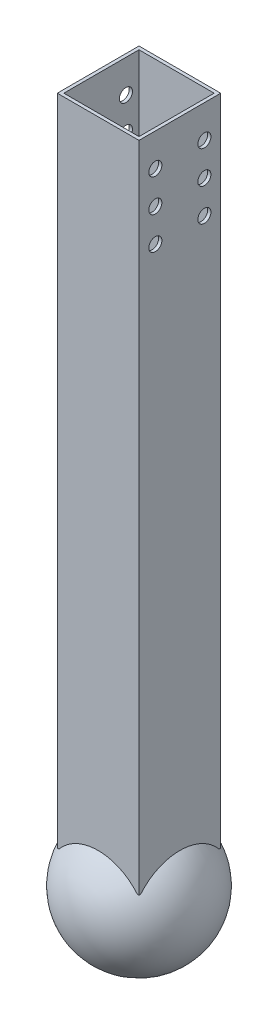
SolidWorks part; units mm, degrees
material "1060 Alloy"
ref_plane "Front Plane" through (0, 0, 0) normal (0, 0, 1) x (1, 0, 0)
ref_plane "Top Plane" through (0, 0, 0) normal (0, 1, 0) x (1, 0, 0)
ref_plane "Right Plane" through (0, 0, 0) normal (1, 0, 0) x (0, 0, -1)
sketch "Sketch1" plane through (0, 0, 0) normal (0, 1, 0) x (1, 0, 0)
  line L0 (-11.5, -11.5) -> (11.5, -11.5)
  line L1 (-12.5, 12.5) -> (12.5, 12.5)
  line L2 (-12.5, 12.5) -> (-12.5, -12.5)
  line L3 (-12.5, -12.5) -> (12.5, -12.5)
  line L4 (12.5, 12.5) -> (12.5, -12.5)
  line L5 (-12.5, 12.5) -> (12.5, -12.5) construction
  line L6 (-12.5, -12.5) -> (12.5, 12.5) construction
  line L7 (11.5, 11.5) -> (11.5, -11.5)
  line L8 (-11.5, 11.5) -> (11.5, 11.5)
  line L9 (-11.5, 11.5) -> (-11.5, -11.5)
  point P0 (0, 0)
  dimension "D1" = 25
  dimension "D2" = 25
  dimension "D3" = 1
extrude "Boss-Extrude1" add sketch "Sketch1" along normal blind 200
ref_plane "Plane1" through (0, -10, 0) normal (0, -1, 0) x (-1, 0, 0)
sketch "Sketch2" plane through (0, -10, 0) normal (0, -1, 0) x (-1, 0, 0)
  line L0 (0, 20) -> (0, -20) construction
  arc A2 (0, -20) -> (0, 20) centre (0, 0) cw
  arc A3 (0, -19) -> (0, 19) centre (0, 0) cw
revolve "Revolve1" add sketch "Sketch2" angle 360 about L0
sketch "Sketch3" plane through (12.5, 0, 0) normal (1, 0, 0) x (0, 0, -1)
  line L0 (0, 0) -> (0, 288.1425) construction
  line L1 (-12.5, 200) -> (12.5, 200) construction
  circle A0 centre (7.5, 190) radius 2
  circle A1 centre (7.5, 180) radius 2
  circle A3 centre (-7.5, 190) radius 2
  circle A5 centre (-7.5, 180) radius 2
  circle A6 centre (7.5, 170) radius 2
  circle A7 centre (-7.5, 170) radius 2
  dimension "D1" = 7.5
  dimension "D5" = 10
  dimension "D11" = 7.5
  dimension "D2" = 7.5
  dimension "D3" = 7.5
  dimension "D4" = 7.5
  dimension "D6" = 7.5
  dimension "D7" = 10
  dimension "D8" = 10
  dimension "D9" = 10
  dimension "D10" = 10
  dimension "D12" = 10
extrude "Cut-Extrude1" cut sketch "Sketch3" against normal blind 25
